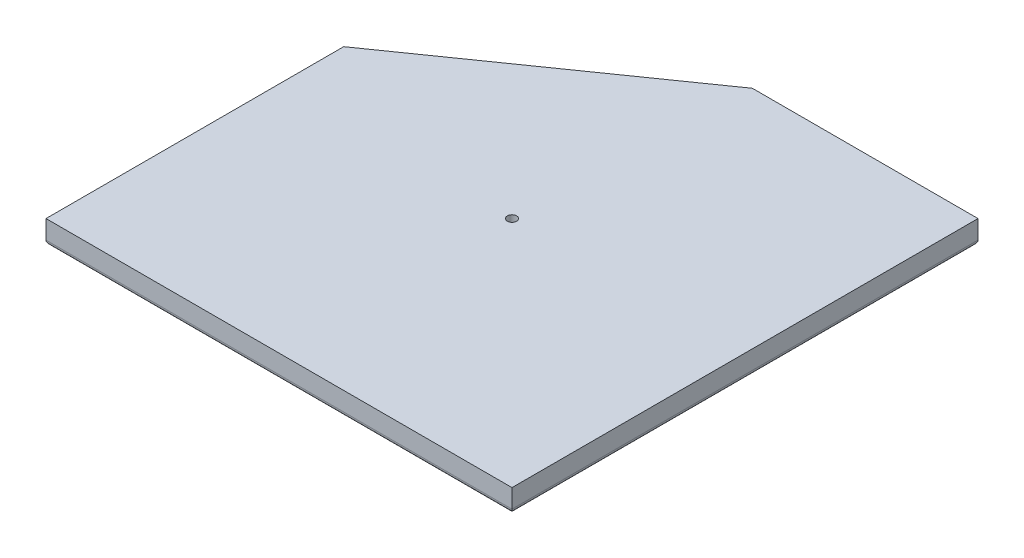
SolidWorks part; units mm, degrees
ref_plane "Front Plane" through (0, 0, 0) normal (0, 0, 1) x (1, 0, 0)
ref_plane "Top Plane" through (0, 0, 0) normal (0, 1, 0) x (1, 0, 0)
ref_plane "Right Plane" through (0, 0, 0) normal (1, 0, 0) x (0, 0, -1)
sketch "Sketch1" plane through (0, 0, 0) normal (0, 1, 0) x (1, 0, 0)
  line L0 (0, 0) -> (100, 0)
  line L1 (100, 0) -> (100, 100)
  line L2 (100, 100) -> (51.5765, 100)
  line L3 (0, 0) -> (0, 63.8858)
  line L4 (51.5765, 100) -> (0, 63.8858)
extrude "Boss-Extrude1" add sketch "Sketch1" along normal blind 5
sketch "Sketch2" plane through (0, 0, 0) normal (0, 1, 0) x (1, 0, 0)
  line L0 (100, 50) -> (0, 50) construction
  line L1 (100, 0) -> (100, 100) construction
  line L2 (0, 63.8858) -> (0, 0) construction
  circle A0 centre (50, 50) radius 1
extrude "Cut-Extrude2" cut sketch "Sketch2" along normal blind 5
fillet "Fillet1" radius 1 5 edges at (0, 0, -31.9429) (50, 0, 0) (100, 0, -50) (75.7882, 0, -100) (25.7882, 0, -81.9429)
